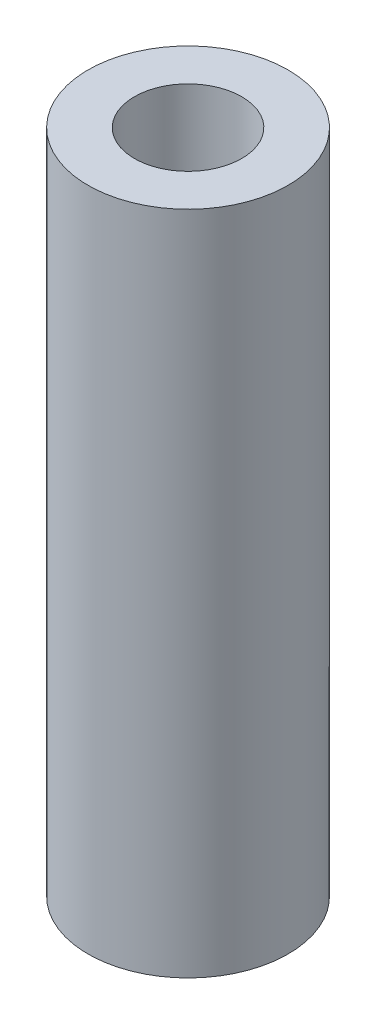
SolidWorks part; units mm, degrees
material "6061-T4 (SS)"
ref_plane "Front" through (0, 0, 0) normal (0, 0, 1) x (1, 0, 0)
ref_plane "Top" through (0, 0, 0) normal (0, 1, 0) x (1, 0, 0)
ref_plane "Right" through (0, 0, 0) normal (1, 0, 0) x (0, 0, -1)
sketch "Sketch1" plane through (0, 0, 0) normal (0, 1, 0) x (1, 0, 0)
  circle A0 centre (0, 0) radius 4.7625
  circle A1 centre (0, 0) radius 2.5527
  dimension "D1" = 9.525
  dimension "D2" = 5.1054
extrude "Boss-Extrude1" add sketch "Sketch1" along normal blind 31.6992
move or copy body "Body-Move/Copy1" bodies to move or copy 101
